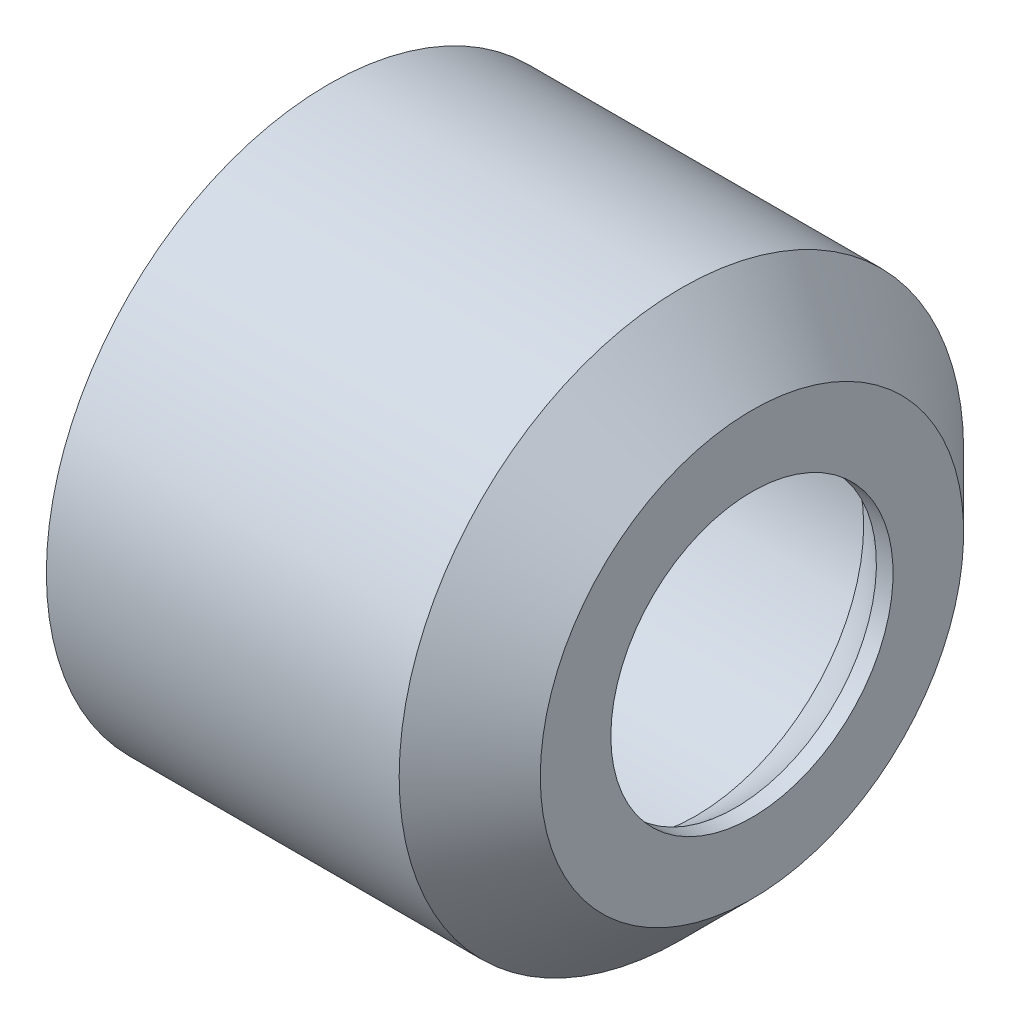
SolidWorks part; units mm, degrees
ref_plane "前视基准面" through (0, 0, 0) normal (0, 0, 1) x (1, 0, 0)
ref_plane "上视基准面" through (0, 0, 0) normal (0, 1, 0) x (1, 0, 0)
ref_plane "右视基准面" through (0, 0, 0) normal (1, 0, 0) x (0, 0, -1)
sketch "草图1" plane through (0, 0, 0) normal (0, 0, 1) x (1, 0, 0)
  line L0 (0, 0) -> (50.9773, 0) construction
  line L1 (32.7373, 12) -> (35.7373, 9)
  line L2 (17.7373, 9) -> (17.7373, 12)
  line L4 (17.7373, 12) -> (32.7373, 12)
  line L5 (35.7373, 9) -> (35.7373, 6)
  line L8 (17.7373, 9) -> (33.3468, 9)
  line L9 (33.3468, 9) -> (33.3468, 7.1394)
  line L11 (35.7373, 6) -> (35.0288, 6)
  arc A1 (35.0288, 6) -> (33.3468, 7.1394) centre (29.7373, 0) ccw
  point P7 (35.7373, 12)
  dimension "D1" = 12
  dimension "D4" = 9
revolve "旋转1" add sketch "草图1" angle 360 about L0
